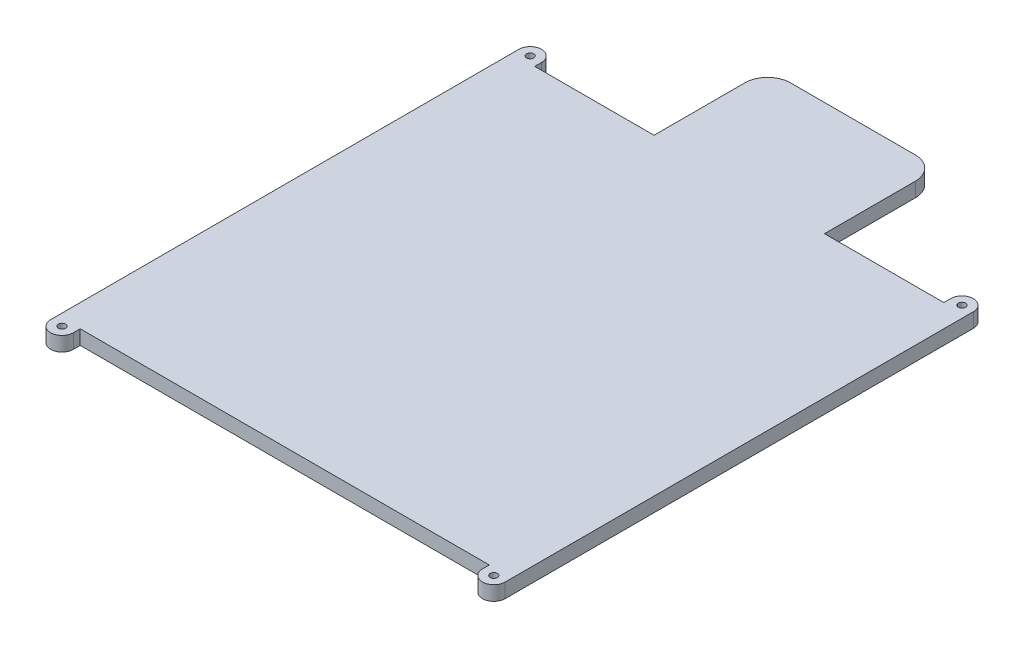
SolidWorks part; units mm, degrees
ref_plane "Plan de face" through (0, 0, 0) normal (0, 0, 1) x (1, 0, 0)
ref_plane "Plan de dessus" through (0, 0, 0) normal (0, 1, 0) x (1, 0, 0)
ref_plane "Plan de droite" through (0, 0, 0) normal (1, 0, 0) x (0, 0, -1)
sketch "Esquisse1" plane through (0, 0, 0) normal (0, 1, 0) x (1, 0, 0)
  line L0 (-100, 0) -> (100, 0) construction
  line L1 (-100, 100) -> (100, 100)
  line L2 (-100, 100) -> (-100, -100)
  line L3 (-100, -100) -> (100, -100)
  line L4 (100, 100) -> (100, -100)
  line L5 (-55, 0) -> (55, 0) construction
  point P6 (0, 0)
  dimension "D1" = 200
extrude "Boss.-Extru.1" add sketch "Esquisse1" along normal blind 6.35
sketch "Esquisse2" plane through (0, 6.35, 0) normal (0, 1, 0) x (1, 0, 0)
  line L0 (-100, 103) -> (-90, 103) construction
  line L1 (-100, 100) -> (-90, 100)
  line L2 (-100, 100) -> (-100, 103)
  line L4 (-90, 100) -> (-90, 103)
  arc A0 (-90, 103) -> (-100, 103) centre (-95, 103) ccw
  dimension "D2" = 5
  dimension "D1" = 3
extrude "Boss.-Extru.2" add sketch "Esquisse2" against normal up to surface (6.35 mm away) up to face at (0, 0, 0)
sketch "Esquisse3" plane through (0, 6.35, 0) normal (0, 1, 0) x (1, 0, 0)
  circle A0 centre (-95, 103) radius 1.5875
  arc A1 (-90, 103) -> (-100, 103) centre (-95, 103) ccw construction
  dimension "D1" = 3.175
extrude "Enlèv. mat.-Extru.1" cut sketch "Esquisse3" against normal up to next
pattern_linear "Répétition linéaire1" count 2 spacing 190 along (1, 0, 0) of "Boss.-Extru.2", "Enlèv. mat.-Extru.1"
mirror "Symétrie1" about plane through (0, 0, 0) normal (0, 0, 1) of "Répétition linéaire1", "Boss.-Extru.2", "Enlèv. mat.-Extru.1"
sketch "Esquisse4" plane through (0, 6.35, 0) normal (0, 1, 0) x (1, 0, 0)
  line L0 (90, 100) -> (-90, 100) construction
  line L1 (-37.5, 100) -> (37.5, 100)
  line L2 (-37.5, 100) -> (-37.5, 150)
  line L3 (-37.5, 150) -> (37.5, 150)
  line L4 (37.5, 100) -> (37.5, 150)
  point P6 (0, 100)
  point P7 (0, 100)
  dimension "D1" = 50
  dimension "D2" = 75
extrude "Boss.-Extru.3" add sketch "Esquisse4" against normal up to surface (6.35 mm away) up to face at (-95, 0, 104.5875)
fillet "Congé1" radius 10 2 edges at (-37.5, 3.175, -150) (37.5, 3.175, -150)
